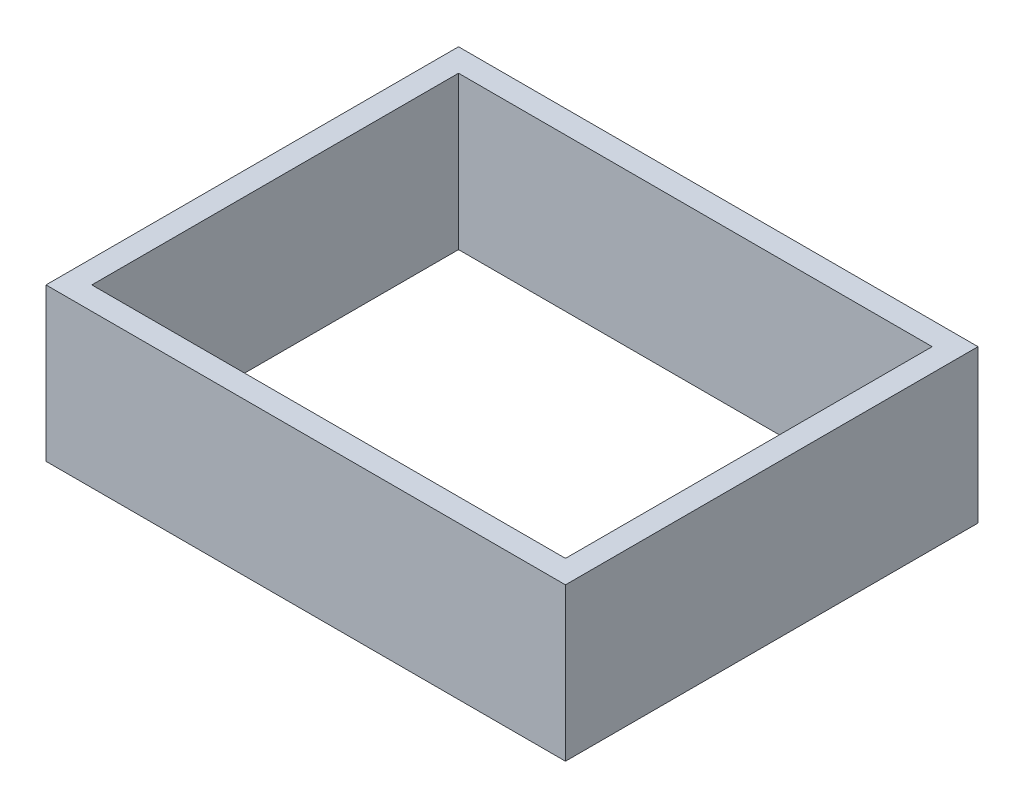
SolidWorks part; units mm, degrees
ref_plane "Front Plane" through (0, 0, 0) normal (0, 0, 1) x (1, 0, 0)
ref_plane "Top Plane" through (0, 0, 0) normal (0, 1, 0) x (1, 0, 0)
ref_plane "Right Plane" through (0, 0, 0) normal (1, 0, 0) x (0, 0, -1)
sketch "Sketch1" plane through (0, 0, 0) normal (0, 1, 0) x (1, 0, 0)
  line L0 (31, 24) -> (-31, 24)
  line L1 (34, -27) -> (-34, -27)
  line L2 (34, -27) -> (34, 27)
  line L3 (34, 27) -> (-34, 27)
  line L4 (-34, -27) -> (-34, 27)
  line L5 (0, 27) -> (0, -27) construction
  line L6 (34, 0) -> (-34, 0) construction
  line L7 (-31, -24) -> (-31, 24)
  line L8 (31, -24) -> (-31, -24)
  line L9 (31, -24) -> (31, 24)
  point P0 (0, 0)
  dimension "D1" = 68
  dimension "D2" = 54
  dimension "D3" = 3
extrude "Boss-Extrude1" add sketch "Sketch1" along normal blind 20
